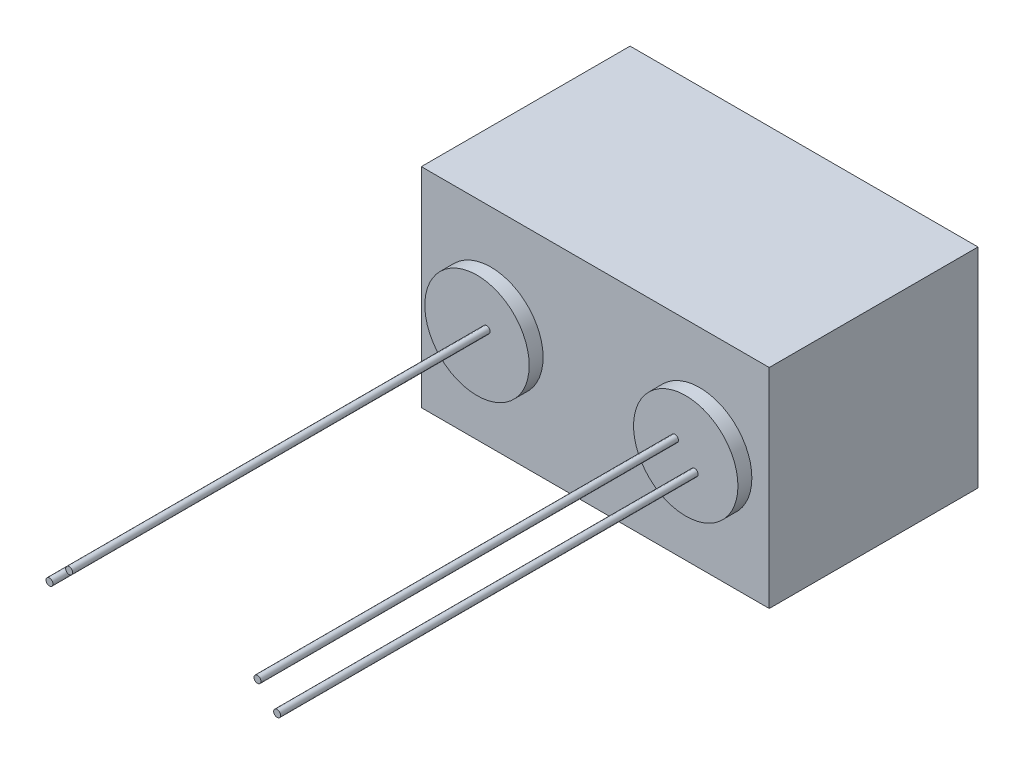
SolidWorks part; units mm, degrees
material "6061-T6 (SS)"
ref_plane "Front Plane" through (0, 0, 0) normal (0, 0, 1) x (1, 0, 0)
ref_plane "Top Plane" through (0, 0, 0) normal (0, 1, 0) x (1, 0, 0)
ref_plane "Right Plane" through (0, 0, 0) normal (1, 0, 0) x (0, 0, -1)
sketch "Sketch1" plane through (0, 0, 0) normal (0, 0, 1) x (1, 0, 0)
  line L0 (-63.5, 0) -> (63.5, 0) construction
  line L1 (-63.5, 38.1) -> (63.5, 38.1)
  line L2 (-63.5, 38.1) -> (-63.5, -38.1)
  line L3 (-63.5, -38.1) -> (63.5, -38.1)
  line L4 (63.5, 38.1) -> (63.5, -38.1)
  point P6 (0, 0)
  dimension "D1" = 127
  dimension "D2" = 76.2
extrude "Boss-Extrude1" add sketch "Sketch1" along normal blind 76.2
sketch "Sketch2" plane through (0, 0, 76.2) normal (0, 0, 1) x (1, 0, 0)
  line L0 (63.5, 0) -> (-63.5, 0) construction
  line L1 (63.5, -38.1) -> (63.5, 38.1) construction
  line L2 (-63.5, 38.1) -> (-63.5, -38.1) construction
  circle A0 centre (38.1, 0) radius 19.05
  circle A1 centre (-38.1, 0) radius 19.05
  dimension "D1" = 38.1
  dimension "D2" = 38.1
  dimension "D3" = 38.1
  dimension "D4" = 38.1
extrude "Boss-Extrude2" add sketch "Sketch2" along normal blind 5.08
sketch "Sketch3" plane through (0, 0, 81.28) normal (0, 0, 1) x (1, 0, 0)
  line L0 (-41.7552, -3.5921) -> (-34.571, 3.5921) construction
  line L1 (41.3506, -3.5921) -> (34.1664, 3.5921) construction
  line L2 (-63.5, 38.1) -> (-63.5, -38.1) construction
  line L3 (63.5, -38.1) -> (63.5, 38.1) construction
  circle A0 centre (41.3506, -3.5921) radius 1.27
  circle A1 centre (34.1664, 3.5921) radius 1.27
  circle A2 centre (-41.7552, -3.5921) radius 1.27
  circle A3 centre (-34.571, 3.5921) radius 1.27
  point P8 (-38.1631, 0)
  point P9 (37.7585, 0)
  point P13 (13.2695, 5.213)
  dimension "D1" = 2.54
  dimension "D2" = 2.54
  dimension "D3" = 2.54
  dimension "D4" = 2.54
  dimension "D5" = 45
  dimension "D6" = 10.16
  dimension "D7" = 45
  dimension "D8" = 10.16
extrude "Boss-Extrude3" add sketch "Sketch3" along normal blind 152.4
